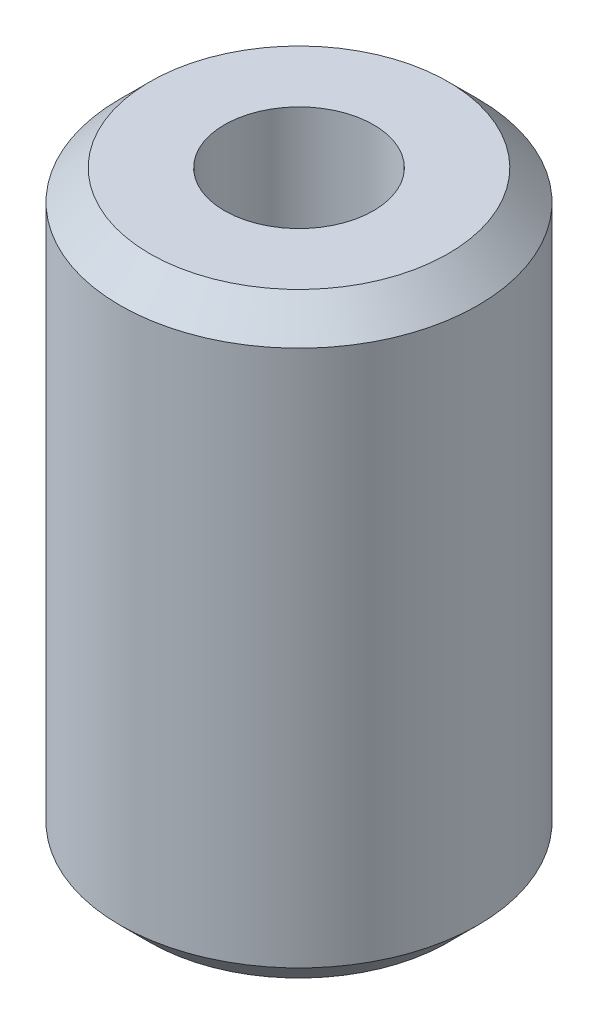
SolidWorks part; units mm, degrees
material "Brass"
ref_plane "Front Plane" through (0, 0, 0) normal (0, 0, 1) x (1, 0, 0)
ref_plane "Top Plane" through (0, 0, 0) normal (0, 1, 0) x (1, 0, 0)
ref_plane "Right Plane" through (0, 0, 0) normal (1, 0, 0) x (0, 0, -1)
sketch "Sketch1" plane through (0, 0, 0) normal (0, 1, 0) x (1, 0, 0)
  circle A0 centre (0, 0) radius 3
  dimension "D1" = 6
extrude "Boss-Extrude1" add sketch "Sketch1" along normal blind 10
hole_wizard "M3x0.5 Tapped Hole1" positions "Sketch2" profile "Sketch3" tap size "M3x0.5" standard "ANSI Metric" end condition through all
sketch "Sketch2" plane through (0, 10, 0) normal (0, 1, 0) x (1, 0, 0)
  point P0 (0, 0)
sketch "Sketch3" plane through (0, 10, 0) normal (1, 0, 0) x (0, 0, 1)
  line L0 (0, 0) -> (0, 10)
  line L1 (0, 10) -> (1.25, 10)
  line L2 (1.25, 10) -> (1.25, 0)
  line L5 (1.25, 0) -> (0, 0)
  line L11 (0, -6.35) -> (0, 107.95) construction
  dimension "Thru Tap Drill Dia." = 2.5
  dimension "Thru Tap Drill Depth" = 10
cosmetic thread "Hole Thread1" parameters "D2"=3
chamfer "Chamfer1" distance 0.5 angle 45 2 edges at (0, 0, 3) (0, 10, 3)
